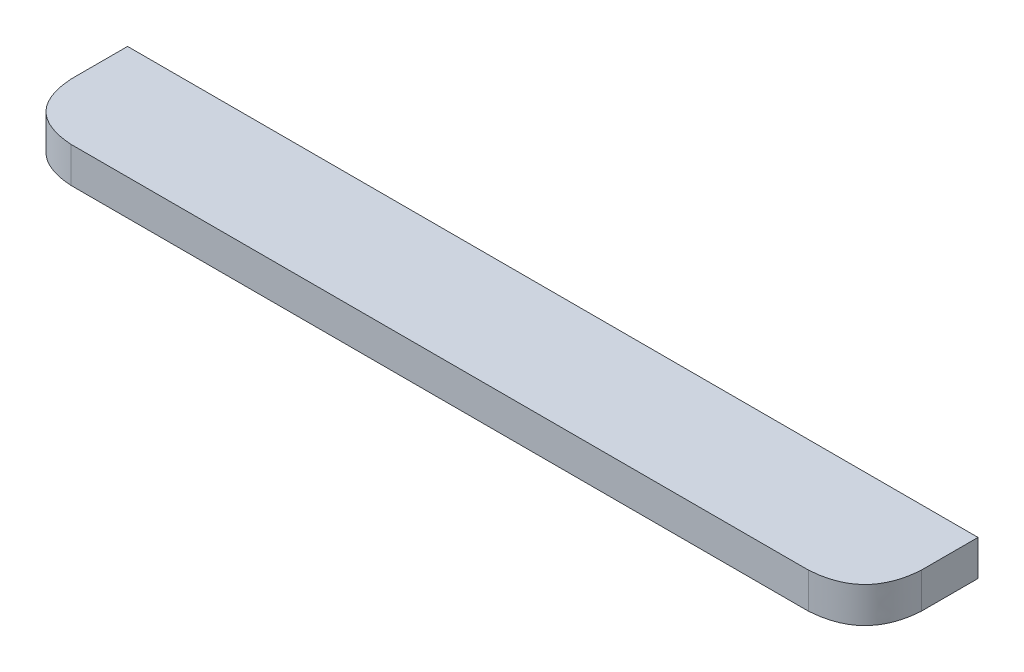
SolidWorks part; units mm, degrees
ref_plane "Front Plane" through (0, 0, 0) normal (0, 0, 1) x (1, 0, 0)
ref_plane "Top Plane" through (0, 0, 0) normal (0, 1, 0) x (1, 0, 0)
ref_plane "Right Plane" through (0, 0, 0) normal (1, 0, 0) x (0, 0, -1)
sketch "Sketch1" plane through (0, 0, 0) normal (0, 1, 0) x (1, 0, 0)
  line L1 (-82.804, -12.7) -> (82.804, -12.7)
  line L2 (-95.504, 0) -> (-95.504, 12.7)
  line L3 (-95.504, 12.7) -> (95.504, 12.7)
  line L4 (95.504, 0) -> (95.504, 12.7)
  line L5 (95.504, 0) -> (82.804, 0) construction
  line L6 (82.804, 0) -> (82.804, -12.7) construction
  line L7 (82.804, 0) -> (91.9639, -9.1599) construction
  line L8 (0, 0) -> (0, -12.7) construction
  line L9 (-95.504, 0) -> (-82.804, 0) construction
  line L10 (-82.804, 0) -> (-82.804, -12.7) construction
  line L11 (-82.804, 0) -> (-91.9639, -9.1599) construction
  spline S0 degree 2 poles (82.804, -12.7) (94.7737, -11.9697) (95.504, 0) knots 0 0 0 1 1 1
  spline S1 degree 2 poles (-82.804, -12.7) (-94.7737, -11.9697) (-95.504, 0) knots 0 0 0 1 1 1
  point P0 (0, 0)
  dimension "D1" = 191.008
extrude "Boss-Extrude1" add sketch "Sketch1" along normal blind 8
